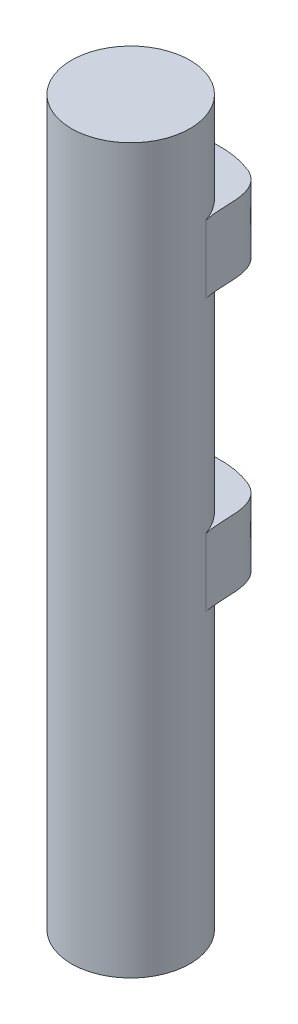
SolidWorks part; units mm, degrees
ref_plane "Front Plane" through (0, 0, 0) normal (0, 0, 1) x (1, 0, 0)
ref_plane "Top Plane" through (0, 0, 0) normal (0, 1, 0) x (1, 0, 0)
ref_plane "Right Plane" through (0, 0, 0) normal (1, 0, 0) x (0, 0, -1)
sketch "Sketch1" plane through (0, 0, 0) normal (0, 1, 0) x (1, 0, 0)
  circle A0 centre (0, 0) radius 25.273
  circle A1 centre (0, 0) radius 25.273
extrude "Boss-Extrude1" add sketch "Sketch1" along normal blind 203.2 contours A0
sketch "Sketch2" plane through (0, 203.2, 0) normal (0, 1, 0) x (1, 0, 0)
  circle A0 centre (0, 0) radius 16.6497
  circle A1 centre (0, 0) radius 25.273 construction
  spline S0 degree 3 poles (-16.1314, 4.1218) (-13.2336, 7.9922) (-17.8746, 25.2503) (1.5488, 26.2881) (6.0478, 24.5387) knots 0 0 0 0 0.459844 1 1 1 1
  spline S1 degree 3 poles (16.1314, 4.1218) (13.5509, 11.4427) (18.5011, 21.9118) (6.0478, 24.5387) knots 0 0 0 0 1 1 1 1
  circle M2 centre (0, 0) radius 25.273
extrude "Cut-Extrude1" cut sketch "Sketch2" against normal blind 203.2 contours S1 A0 S0 M2
ref_plane "Plane1" through (0, 177.8, 0) normal (0, 1, 0) x (1, 0, 0)
ref_plane "Plane2" through (0, 101.6, 0) normal (0, 1, 0) x (1, 0, 0)
sketch "Sketch3" plane through (0, 177.8, 0) normal (0, 1, 0) x (1, 0, 0)
  circle A0 centre (0, 0) radius 16.6497
extrude "Cut-Extrude5" cut sketch "Sketch3" along normal blind 50.8 flip side to cut contours A0
sketch "Sketch4" plane through (0, 101.6, 0) normal (0, 1, 0) x (1, 0, 0)
  circle A0 centre (0, 0) radius 16.6497
extrude "Cut-Extrude6" cut sketch "Sketch4" along normal blind 57.15 flip side to cut
ref_plane "Plane3" through (0, 82.55, 0) normal (0, -1, 0) x (-1, 0, 0)
sketch "Sketch5" plane through (0, 0, 0) normal (0, -1, 0) x (-1, 0, 0)
  circle A0 centre (0, 0) radius 16.6497
extrude "Cut-Extrude7" cut sketch "Sketch5" against normal blind 82.55 flip side to cut
